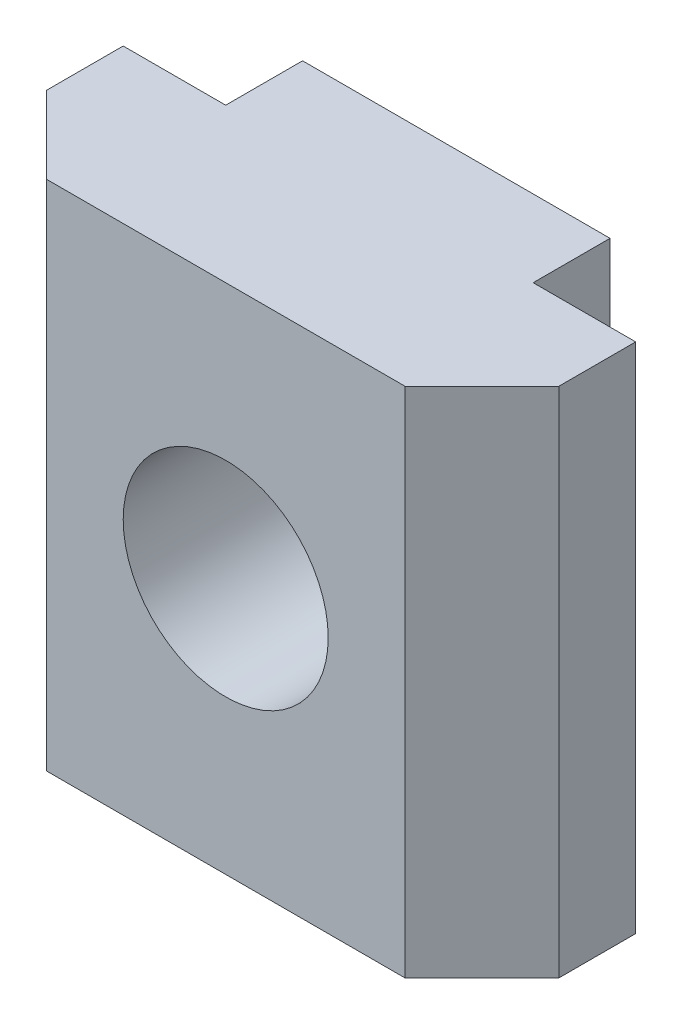
SolidWorks part; units mm, degrees
ref_plane "前视基准面" through (0, 0, 0) normal (0, 0, 1) x (1, 0, 0)
ref_plane "上视基准面" through (0, 0, 0) normal (0, 1, 0) x (1, 0, 0)
ref_plane "右视基准面" through (0, 0, 0) normal (1, 0, 0) x (0, 0, -1)
sketch "草图1" plane through (0, 0, 0) normal (0, 1, 0) x (1, 0, 0)
  line L0 (-3.5, 0) -> (3.5, 0)
  line L1 (3.5, 0) -> (5, 1.5)
  line L2 (-3.5, 0) -> (-5, 1.5)
  line L3 (-5, 1.5) -> (-5, 3)
  line L4 (-5, 3) -> (-3, 3)
  line L5 (-3, 3) -> (-3, 4.5)
  line L6 (-3, 4.5) -> (3, 4.5)
  line L7 (3, 4.5) -> (3, 3)
  line L8 (3, 3) -> (5, 3)
  line L9 (5, 3) -> (5, 1.5)
  point P4 (0, 0)
  dimension "D1" = 7
  dimension "D2" = 1.5
  dimension "D3" = 135
  dimension "D4" = 1.5
  dimension "D5" = 135
  dimension "D6" = 1.5
  dimension "D7" = 6
  dimension "D8" = 2
  dimension "D9" = 1.5
  dimension "D10" = 1.5
extrude "凸台-拉伸1" add sketch "草图1" along normal blind 10
sketch "草图2" plane through (0, 0, 0) normal (0, 0, 1) x (1, 0, 0)
  line L0 (5, 10) -> (5, 0) construction
  line L1 (-3.5, 0) -> (3.5, 0) construction
  circle A0 centre (0, 5) radius 2
  point P4 (5, 5)
  dimension "D3" = 4
  dimension "D1" = 5
  dimension "D2" = 5
extrude "切除-拉伸1" cut sketch "草图2" against normal through all
